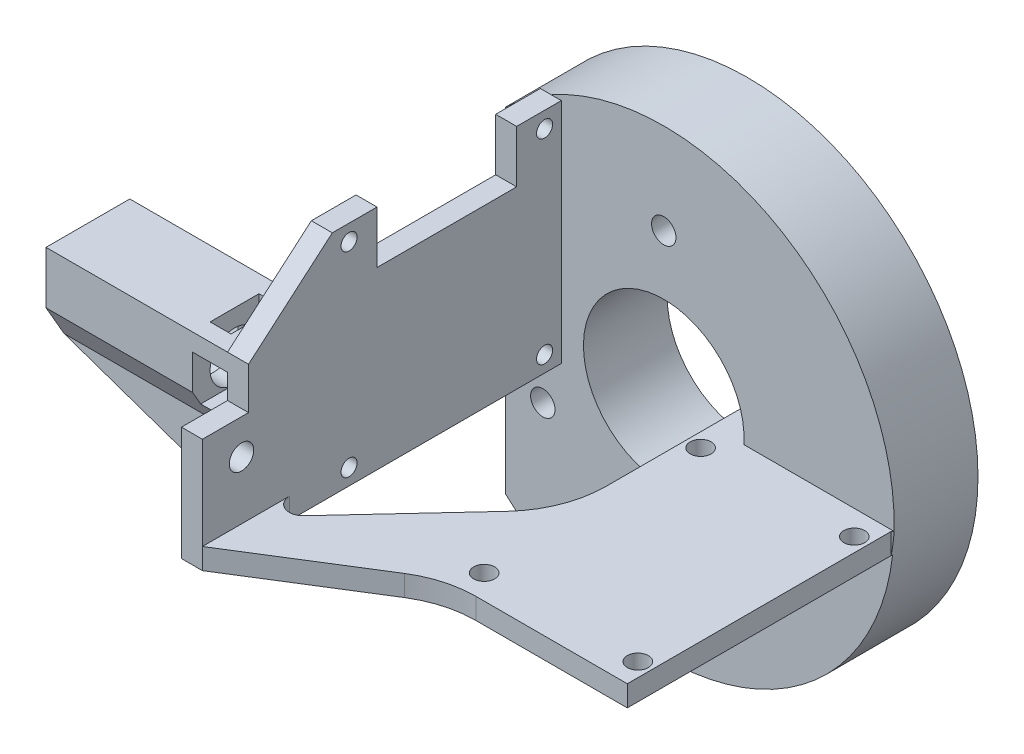
SolidWorks part; units mm, degrees
ref_plane "前视基准面" through (0, 0, 0) normal (0, 0, 1) x (1, 0, 0)
ref_plane "上视基准面" through (0, 0, 0) normal (0, 1, 0) x (1, 0, 0)
ref_plane "右视基准面" through (0, 0, 0) normal (1, 0, 0) x (0, 0, -1)
sketch "草图1" plane through (0, 0, 0) normal (0, 0, 1) x (1, 0, 0)
  circle A0 centre (0, 0) radius 29
  dimension "D1" = 58
extrude "凸台-拉伸1" add sketch "草图1" along normal blind 5
sketch "草图2" plane through (0, 0, 5) normal (0, 0, 1) x (1, 0, 0)
  line L0 (0, 0) -> (0, 20)
  line L1 (0, 0) -> (-17.3205, -10)
  line L2 (0, 0) -> (17.3205, -10)
  circle A0 centre (0, 0) radius 20
  dimension "D1" = 40
  dimension "D2" = 120
  dimension "D3" = 120
sketch "草图3" plane through (0, 0, 5) normal (0, 0, 1) x (1, 0, 0)
  point P0 (0, 20)
  point P3 (-17.3205, -10)
  point P6 (17.3205, -10)
hole_wizard "孔1" positions "草图3" profile "草图4" legacy end condition up to next
sketch "草图4" plane through (0, 20, 5) normal (1, 0, 0) x (0, -1, 0)
  line L0 (0, 0) -> (0, 5)
  line L1 (0, 5) -> (1.75, 5)
  line L2 (1.75, 5) -> (1.75, 0)
  line L3 (1.75, 0) -> (0, 0)
  line L4 (0, 110) -> (0, -10) construction
  dimension "直径" = 3.5
  dimension "深度" = 5
hole_wizard "孔2" positions "草图5" profile "草图6" legacy end condition up to next
sketch "草图5" plane through (0, 0, 5) normal (0, 0, 1) x (1, 0, 0)
  point P0 (0, 0)
sketch "草图6" plane through (0, 0, 5) normal (1, 0, 0) x (0, -1, 0)
  line L0 (0, 0) -> (0, 5)
  line L1 (0, 5) -> (11.5, 5)
  line L2 (11.5, 5) -> (11.5, 0)
  line L3 (11.5, 0) -> (0, 0)
  line L4 (0, 110) -> (0, -10) construction
  dimension "直径" = 23
  dimension "深度" = 5
sketch "草图7" plane through (0, 0, 5) normal (0, 0, 1) x (1, 0, 0)
  line L1 (-28.892, -2.5) -> (28.892, -2.5)
  line L2 (-28.892, -2.5) -> (-28.892, 2.5)
  line L3 (-28.892, 2.5) -> (28.892, 2.5)
  line L4 (28.892, -2.5) -> (28.892, 2.5)
  line L5 (-28.892, -2.5) -> (28.892, 2.5) construction
  line L6 (-28.892, 2.5) -> (28.892, -2.5) construction
  circle A0 centre (0, 0) radius 29 construction
  circle A1 centre (0, 0) radius 11.4884
  circle A2 centre (0, 0) radius 29
  point P0 (0, 0)
  circle M5 centre (0, 0) radius 11.5
  dimension "D2" = 58
  dimension "D1" = 5
extrude "凸台-拉伸3" add sketch "草图7" along normal blind 65 contours L3 L2 L1 M5 | A2
sketch "草图9" plane through (0, 0, 5) normal (0, 0, 1) x (1, 0, 0)
  line L1 (-28.892, 2.5) -> (-29.892, 2.5)
  line L2 (-28.892, 2.5) -> (-28.892, -2.5)
  line L3 (-28.892, -2.5) -> (-29.892, -2.5)
  line L4 (-29.892, 2.5) -> (-29.892, -2.5)
  dimension "D1" = 5
  dimension "D2" = 1
extrude "切除-拉伸1" cut sketch "草图9" against normal blind 10
sketch "草图10" plane through (0, 2.5, 0) normal (0, 1, 0) x (1, 0, 0)
  line L0 (-28.892, -70) -> (-11.225, -70) construction
  line L1 (-28.892, -5) -> (-25.892, -5)
  line L2 (-28.892, -5) -> (-28.892, -70)
  line L3 (-28.892, -70) -> (-25.892, -70)
  line L4 (-25.892, -5) -> (-25.892, -70)
  dimension "D1" = 3
extrude "凸台-拉伸5" add sketch "草图10" along normal blind 10
sketch "草图11" plane through (-28.892, 0, 0) normal (-1, 0, 0) x (0, 0, 1)
  line L0 (10, 7.5) -> (64.4, 7.5) construction
  line L1 (5, 2.5) -> (10, 2.5) construction
  line L2 (5, 2.5) -> (5, 7.5) construction
  line L3 (5, 7.5) -> (10, 7.5) construction
  line L4 (10, 2.5) -> (10, 7.5) construction
  line L5 (57.4, 7.5) -> (57.4, 12.5)
  point P5 (57.4, 7.5)
  dimension "D1" = 5
  dimension "D2" = 5
  dimension "D3" = 54.4
  dimension "D4" = 7
  dimension "D5" = 5
sketch "草图14" plane through (-28.892, 0, 0) normal (-1, 0, 0) x (0, 0, 1)
  point P0 (10, 7.5)
  point P3 (64.4, 7.5)
hole_wizard "孔3" positions "草图14" profile "草图15" legacy end condition up to next
sketch "草图15" plane through (-28.892, 7.5, 10) normal (0, 1, 0) x (0, 0, 1)
  line L0 (0, 0) -> (0, 3)
  line L1 (0, 3) -> (1.75, 3)
  line L2 (1.75, 3) -> (1.75, 0)
  line L3 (1.75, 0) -> (0, 0)
  line L4 (0, 110) -> (0, -10) construction
  dimension "直径" = 3.5
  dimension "深度" = 3
sketch "草图16" plane through (-28.892, 0, 0) normal (-1, 0, 0) x (0, 0, 1)
  line L0 (5, 12.5) -> (70, 12.5) construction
  line L1 (25, 12.5) -> (45, 12.5)
  line L2 (25, 12.5) -> (25, 9.5)
  line L3 (25, 9.5) -> (45, 9.5)
  line L4 (45, 12.5) -> (45, 9.5)
  line L5 (5, -20) -> (5, 20) construction
  dimension "D1" = 20
  dimension "D2" = 20
  dimension "D3" = 3
sketch "草图17" plane through (-28.892, 0, 0) normal (-1, 0, 0) x (0, 0, 1)
  line L0 (5, 0) -> (25, 0) construction
  line L1 (5, 2.5) -> (70, 2.5) construction
  line L2 (5, 2.5) -> (5, -2.5)
  line L3 (5, -2.5) -> (70, -2.5)
  line L4 (70, 2.5) -> (70, -2.5)
  line L5 (25, 0) -> (45, 0) construction
  dimension "D1" = 20
  dimension "D2" = 20
sketch "草图20" plane through (0, 0, 70) normal (0, 0, 1) x (1, 0, 0)
  line L0 (-11.225, 2.5) -> (-11.225, -2.5)
  circle A0 centre (0, 0) radius 11.5
  arc M8 (-11.225, -2.5) -> (-11.225, 2.5) centre (0, 0) cw
extrude "凸台-拉伸6" add sketch "草图20" against normal blind 65 contours L0 M8
sketch "草图21" plane through (-28.892, 0, 0) normal (-1, 0, 0) x (0, 0, 1)
  line L0 (63.4, 11) -> (60.8019, 6.5) construction
  line L1 (51.4, 6.5) -> (63.4, 6.5) construction
  line L2 (51.4, 6.5) -> (51.4, 18.5) construction
  line L3 (51.4, 18.5) -> (63.4, 18.5) construction
  line L4 (63.4, 6.5) -> (63.4, 18.5) construction
  line L5 (51.4, 6.5) -> (63.4, 18.5) construction
  line L6 (51.4, 18.5) -> (63.4, 6.5) construction
  circle A0 centre (57.4, 12.5) radius 5.2 construction
  point P0 (57.4, 12.5)
  dimension "D3" = 10.4
  dimension "D1" = 12
  dimension "D2" = 12
  dimension "D4" = 30
  dimension "D5" = 4.5
sketch "草图22" plane through (-28.892, 0, 0) normal (-1, 0, 0) x (0, 0, 1)
  line L0 (51.4, 6.5) -> (51.4, 18.5) construction
  line L1 (51.4, 12.5) -> (63.4, 12.5)
  line L2 (51.4, 12.5) -> (51.4, 18.5)
  line L3 (51.4, 18.5) -> (63.4, 18.5)
  line L4 (63.4, 12.5) -> (63.4, 18.5)
extrude "凸台-拉伸7" add sketch "草图22" against normal blind 3 contours L2 L1 L4 L3
sketch "草图23" plane through (-28.892, 0, 0) normal (-1, 0, 0) x (0, 0, 1)
  line L0 (60.8019, 6.5) -> (63.4, 11)
  line L1 (51.4, 18.5) -> (63.4, 18.5)
  line L2 (51.4, 18.5) -> (51.4, 6.5)
  line L3 (51.4, 6.5) -> (63.4, 6.5)
  line L4 (63.4, 18.5) -> (63.4, 6.5)
  line M16 (63.4, 12.5) -> (63.4, 18.5)
  line M17 (63.4, 18.5) -> (51.4, 18.5)
  line M18 (51.4, 18.5) -> (51.4, 12.5)
extrude "凸台-拉伸8" add sketch "草图23" along normal blind 8 contours L4 L2 L3 L0 M16 M17 M18
hole_wizard "孔5" positions "草图25" profile "草图26" legacy
sketch "草图25" plane through (-36.892, 0, 0) normal (-1, 0, 0) x (0, 0, 1)
  point P0 (57.4, 12.5)
sketch "草图26" plane through (-36.892, 12.5, 57.4) normal (0, 1, 0) x (0, 0, 1)
  line L0 (0, 0) -> (0, 3)
  line L1 (0, 3) -> (3.5, 3)
  line L2 (3.5, 3) -> (3.5, 0)
  line L3 (3.5, 0) -> (0, 0)
  line L4 (0, 110) -> (0, -10) construction
  dimension "直径" = 7
  dimension "深度" = 3
sketch "草图27" plane through (0, 0, 51.4) normal (0, 0, -1) x (-1, 0, 0)
  line L0 (36.892, 12.5) -> (28.892, 12.5)
  line L1 (36.892, 18.5) -> (36.892, 6.5) construction
  line L3 (28.892, 9) -> (33.892, 9)
  line L4 (28.892, 9) -> (28.892, 16)
  line L5 (28.892, 16) -> (33.892, 16)
  line L6 (33.892, 9) -> (33.892, 16)
  line L7 (28.892, 9) -> (33.892, 16) construction
  line L8 (28.892, 16) -> (33.892, 9) construction
  point P5 (31.392, 12.5)
  line M6 (28.892, 12.5) -> (28.892, 6.5)
  dimension "D1" = 3
  dimension "D2" = 5
  dimension "D3" = 7
extrude "切除-拉伸3" cut sketch "草图27" against normal through all contours L0 L6 L5 L4 | L3 L6 L0 M6
sketch "草图28" plane through (0, 18.5, 0) normal (0, 1, 0) x (1, 0, 0)
  line L0 (-36.892, -57.4) -> (-28.892, -57.4)
  line L1 (-36.892, -63.4) -> (-36.892, -51.4) construction
  line L3 (-33.892, -60.9) -> (-30.892, -60.9)
  line L4 (-33.892, -60.9) -> (-33.892, -53.9)
  line L5 (-33.892, -53.9) -> (-30.892, -53.9)
  line L6 (-30.892, -60.9) -> (-30.892, -53.9)
  line L7 (-33.892, -60.9) -> (-30.892, -53.9) construction
  line L8 (-33.892, -53.9) -> (-30.892, -60.9) construction
  point P5 (-32.392, -57.4)
  dimension "D1" = 3
  dimension "D2" = 3
  dimension "D3" = 7
extrude "切除-拉伸4" cut sketch "草图28" against normal up to next contours L3 L6 L0 L4 | L0 L6 L5 L4
sketch "草图29" plane through (-36.892, 0, 0) normal (-1, 0, 0) x (0, 0, 1)
  line L0 (51.4, 18.5) -> (63.4, 6.5) construction
  line L1 (51.4, 6.5) -> (63.4, 6.5)
  line L2 (51.4, 6.5) -> (51.4, 18.5)
  line L3 (51.4, 18.5) -> (63.4, 18.5)
  line L4 (63.4, 6.5) -> (63.4, 18.5)
  line L5 (51.4, 6.5) -> (63.4, 18.5) construction
  line L6 (51.4, 18.5) -> (63.4, 6.5) construction
  line L7 (60.8019, 6.5) -> (63.4, 11)
  point P0 (57.4, 12.5)
  circle M5 centre (57.4, 12.5) radius 3.5
  line M6 (63.4, 11) -> (63.4, 18.5)
  line M7 (63.4, 18.5) -> (51.4, 18.5)
  line M8 (51.4, 18.5) -> (51.4, 6.5)
  line M9 (51.4, 6.5) -> (60.8019, 6.5)
  line M10 (60.8019, 6.5) -> (63.4, 11)
extrude "凸台-拉伸9" add sketch "草图29" along normal blind 18 contours M10 M6 M7 M8 M9 M5 | M5
sketch "草图30" plane through (-54.892, 0, 0) normal (-1, 0, 0) x (0, 0, 1)
  point P0 (57.4, 12.5)
hole_wizard "孔6" positions "草图30" profile "草图31" legacy
sketch "草图31" plane through (-54.892, 12.5, 57.4) normal (0, 1, 0) x (0, 0, 1)
  line L0 (0, 0) -> (0, 18)
  line L1 (0, 18) -> (5.1, 18)
  line L2 (5.1, 18) -> (5.1, 0)
  line L3 (5.1, 0) -> (0, 0)
  line L4 (0, 110) -> (0, -10) construction
  dimension "直径" = 10.2
  dimension "深度" = 18
sketch "草图32" plane through (0, 6.5, 0) normal (0, -1, 0) x (1, 0, 0)
  line L0 (-28.892, 10) -> (-28.892, 64.4) construction
  line L1 (-54.892, 60.8019) -> (-28.892, 60.8019)
  line L2 (-54.892, 60.8019) -> (-54.892, 55.8019)
  line L3 (-54.892, 55.8019) -> (-28.892, 55.8019)
  line L4 (-28.892, 60.8019) -> (-28.892, 55.8019)
  dimension "D1" = 5
extrude "凸台-拉伸10" add sketch "草图32" along normal blind 9
sketch "草图33" plane through (0, 0, 60.8019) normal (0, 0, 1) x (1, 0, 0)
  line L0 (-54.892, 6.5) -> (-28.892, -2.5)
  line L1 (-28.892, -2.5) -> (-54.892, -2.5)
  line L2 (-54.892, -2.5) -> (-54.892, 6.5)
extrude "切除-拉伸5" cut sketch "草图33" against normal up to next contours L2 L0 L1
sketch "草图36" plane through (-28.892, 0, 0) normal (-1, 0, 0) x (0, 0, 1)
  line L0 (25, 12.5) -> (45, 12.5) construction
  line L1 (18.6, 28.8) -> (51.4, 28.8)
  line L2 (18.6, 28.8) -> (18.6, -3.8)
  line L3 (18.6, -3.8) -> (51.4, -3.8)
  line L4 (51.4, 28.8) -> (51.4, -3.8)
  line L5 (18.6, 28.8) -> (51.4, -3.8) construction
  line L6 (18.6, -3.8) -> (51.4, 28.8) construction
  line L7 (51.4, 6.5) -> (51.4, 18.5) construction
  point P0 (35, 12.5)
  dimension "D2" = 32.6
extrude "凸台-拉伸12" add sketch "草图36" against normal blind 3
sketch "草图38" plane through (0, 0, 0) normal (0, 0, -1) x (-1, 0, 0)
  circle A0 centre (0, 0) radius 29
extrude "切除-拉伸7" cut sketch "草图38" against normal blind 5
sketch "草图39" plane through (0, 0, 5) normal (0, 0, -1) x (-1, 0, 0)
  line L1 (11.225, -2.5) -> (28.892, -2.5)
  line L2 (11.225, -2.5) -> (11.225, 12.5)
  line L3 (11.225, 12.5) -> (28.892, 12.5)
  line L4 (28.892, -2.5) -> (28.892, 12.5)
extrude "切除-拉伸8" cut sketch "草图39" against normal up to surface (13.6 mm away) up to face at (-27.392, 20.65, 18.6)
sketch "草图41" plane through (0, 0, 18.6) normal (0, 0, -1) x (-1, 0, 0)
  line L0 (11.225, -2.5) -> (11.225, 2.5) construction
  circle A0 centre (11.225, 0) radius 33
  dimension "D1" = 66
extrude "凸台-拉伸14" add sketch "草图41" along normal blind 12
sketch "草图42" plane through (0, 0, 6.6) normal (0, 0, -1) x (-1, 0, 0)
  line L0 (11.225, 0) -> (11.225, 20)
  line L1 (11.225, 0) -> (-6.0955, -10)
  line L2 (11.225, 0) -> (28.5455, -10)
  circle A0 centre (11.225, 0) radius 20
  dimension "D1" = 40
  dimension "D2" = 120
  dimension "D3" = 120
sketch "草图45" plane through (0, 0, 6.6) normal (0, 0, -1) x (-1, 0, 0)
  point P0 (11.225, 20)
  point P3 (-6.0955, -10)
  point P6 (28.5455, -10)
hole_wizard "孔8" positions "草图45" profile "草图46" legacy end condition up to next
sketch "草图46" plane through (-11.225, 20, 6.6) normal (1, 0, 0) x (0, 1, 0)
  line L0 (0, 0) -> (0, 12)
  line L1 (0, 12) -> (1.75, 12)
  line L2 (1.75, 12) -> (1.75, 0)
  line L3 (1.75, 0) -> (0, 0)
  line L4 (0, 110) -> (0, -10) construction
  dimension "直径" = 3.5
  dimension "深度" = 12
sketch "草图47" plane through (0, 0, 6.6) normal (0, 0, -1) x (-1, 0, 0)
  point P0 (11.225, 0)
hole_wizard "孔9" positions "草图47" profile "草图48" legacy end condition through all
sketch "草图48" plane through (-11.225, 0, 6.6) normal (1, 0, 0) x (0, 1, 0)
  line L0 (0, 0) -> (0, 63.4)
  line L1 (0, 63.4) -> (11.5, 63.4)
  line L2 (11.5, 63.4) -> (11.5, 0)
  line L3 (11.5, 0) -> (0, 0)
  line L4 (0, 110) -> (0, -10) construction
  dimension "直径" = 23
  dimension "深度" = 63.4
sketch "草图50" plane through (-28.892, 0, 0) normal (-1, 0, 0) x (0, 0, 1)
  line L0 (18.6, 28.8) -> (51.4, -3.8)
  line L2 (21, 26.5) -> (49, 26.5)
  line L3 (21, 26.5) -> (21, -1.5)
  line L4 (21, -1.5) -> (49, -1.5)
  line L5 (49, 26.5) -> (49, -1.5)
  line L6 (21, 26.5) -> (49, -1.5) construction
  line L7 (21, -1.5) -> (49, 26.5) construction
  circle A0 centre (21, 26.5) radius 1.5
  circle A1 centre (49, 26.5) radius 1.5
  circle A2 centre (49, -1.5) radius 1.5
  circle A3 centre (21, -1.5) radius 1.5
  point P4 (35, 12.5)
  dimension "D3" = 3
  dimension "D4" = 3
  dimension "D5" = 3
  dimension "D6" = 3
  dimension "D1" = 28
  dimension "D2" = 28
sketch "草图51" plane through (-28.892, 0, 0) normal (-1, 0, 0) x (0, 0, 1)
  point P0 (21, 26.5)
  point P3 (49, 26.5)
  point P6 (49, -1.5)
  point P9 (21, -1.5)
hole_wizard "孔10" positions "草图51" profile "草图52" legacy end condition through all
sketch "草图52" plane through (-28.892, 26.5, 21) normal (0, 1, 0) x (0, 0, 1)
  line L0 (0, 0) -> (0, 50.6671)
  line L1 (0, 50.6671) -> (1.15, 50.6671)
  line L2 (1.15, 50.6671) -> (1.15, 0)
  line L3 (1.15, 0) -> (0, 0)
  line L4 (0, 110) -> (0, -10) construction
  dimension "直径" = 2.3
  dimension "深度" = 50.6671
sketch "草图53" plane through (-28.892, 0, 0) normal (-1, 0, 0) x (0, 0, 1)
  line L0 (51.4, 28.8) -> (18.6, 28.8) construction
  line L1 (25, 36.3) -> (45, 36.3)
  line L2 (25, 36.3) -> (25, 21.3)
  line L3 (25, 21.3) -> (45, 21.3)
  line L4 (45, 36.3) -> (45, 21.3)
  line L5 (25, 36.3) -> (45, 21.3) construction
  line L6 (25, 21.3) -> (45, 36.3) construction
  point P0 (35, 28.8)
  dimension "D1" = 20
  dimension "D2" = 15
extrude "切除-拉伸9" cut sketch "草图53" against normal blind 3
sketch "草图55" plane through (-25.892, 0, 0) normal (1, 0, 0) x (0, 0, -1)
  line L0 (-51.4, 28.8) -> (-63.4, 18.5)
  line L1 (-63.4, 18.5) -> (-51.4, 18.5)
  line L2 (-51.4, 18.5) -> (-51.4, 28.8)
extrude "凸台-拉伸16" add sketch "草图55" against normal blind 3
sketch "草图56" plane through (0, 2.5, 0) normal (0, 1, 0) x (1, 0, 0)
  line L1 (-25.892, -18.6) -> (-22.4499, -18.6)
  line L2 (-25.892, -18.6) -> (-25.892, -70)
  line L3 (-25.892, -70) -> (-22.4499, -70)
  line L4 (-22.4499, -18.6) -> (-22.4499, -70)
extrude "切除-拉伸10" cut sketch "草图56" against normal through all
sketch "草图57" plane through (0, 0, 51.4) normal (0, 0, 1) x (1, 0, 0)
  line L0 (-28.892, -2.5) -> (-25.892, -2.5) construction
  line L1 (-28.892, -3.8) -> (-25.892, -3.8)
  line L2 (-28.892, -3.8) -> (-28.892, -2.5)
  line L3 (-28.892, -2.5) -> (-25.892, -2.5)
  line L4 (-25.892, -3.8) -> (-25.892, -2.5)
  line L5 (-25.892, 28.8) -> (-25.892, -3.8) construction
extrude "凸台-拉伸17" add sketch "草图57" along normal up to surface (18.6 mm away) up to face at (-27.392, 5, 70)
sketch "草图58" plane through (0, -3.8, 0) normal (0, -1, 0) x (1, 0, 0)
  line L0 (-25.892, 70) -> (21.775, 18.6)
  line L1 (-25.892, 62.6468) -> (14.9559, 18.6)
  line L2 (-25.892, 18.6) -> (-25.892, 70) construction
  line L3 (21.775, 18.6) -> (-44.225, 18.6) construction
  line L4 (-25.892, 70) -> (-25.892, 62.6468)
  line L5 (14.9559, 18.6) -> (21.775, 18.6)
  dimension "D1" = 5
extrude "凸台-拉伸18" add sketch "草图58" against normal blind 3
ref_plane "基准面1" through (-13.892, 0, 0) normal (1, 0, 0) x (0, 0, -1)
sketch "草图62" plane through (0, 0, 6.6) normal (0, 0, -1) x (-1, 0, 0)
  line L0 (33.892, 23.9834) -> (33.892, -23.9834)
  line L1 (11.225, 0) -> (11.225, 20) construction
  line L2 (13.892, 17.93) -> (13.892, -17.93) construction
  circle A0 centre (11.225, 0) radius 33 construction
  circle A1 centre (11.225, 0) radius 33
  dimension "D2" = 66
  dimension "D1" = 20
extrude "切除-拉伸11" cut sketch "草图62" against normal up to next contours L0 A1
sketch "草图63" plane through (0, 0, 18.6) normal (0, 0, 1) x (1, 0, 0)
  line L0 (21.775, -2.3) -> (0.0427, -2.3)
  line L1 (21.775, -0.8) -> (21.775, -3.8) construction
  line L2 (21.775, -0.8) -> (-25.892, -0.8) construction
  line L4 (21.5555, -3.8) -> (-4.4445, -3.8)
  line L9 (21.5555, -3.8) -> (21.5555, -0.8)
  line L10 (21.5555, -0.8) -> (-4.4445, -0.8)
  line L11 (-4.4445, -3.8) -> (-4.4445, -0.8)
  circle A0 centre (-11.225, 0) radius 11.5 construction
  point P13 (21.5555, -3.8)
  dimension "D1" = 26
extrude "凸台-拉伸21" add sketch "草图63" along normal blind 38 contours L4 L11 L10 L9
sketch "草图64" plane through (0, -0.8, 0) normal (0, 1, 0) x (1, 0, 0)
  line L0 (-4.4445, -18.6) -> (21.5555, -56.6)
  line L2 (-2.4445, -53.1) -> (19.5555, -53.1)
  line L3 (-2.4445, -53.1) -> (-2.4445, -22.1)
  line L4 (-2.4445, -22.1) -> (19.5555, -22.1)
  line L5 (19.5555, -53.1) -> (19.5555, -22.1)
  line L6 (-2.4445, -53.1) -> (19.5555, -22.1) construction
  line L7 (-2.4445, -22.1) -> (19.5555, -53.1) construction
  point P4 (8.5555, -37.6)
  dimension "D1" = 22
  dimension "D2" = 31
sketch "草图65" plane through (0, -0.8, 0) normal (0, 1, 0) x (1, 0, 0)
  point P0 (-2.4445, -22.1)
  point P3 (19.5555, -22.1)
  point P6 (-2.4445, -53.1)
  point P9 (19.5555, -53.1)
hole_wizard "孔11" positions "草图65" profile "草图66" legacy end condition up to next
sketch "草图66" plane through (-2.4445, -0.8, 22.1) normal (1, 0, 0) x (0, 0, 1)
  line L0 (0, 0) -> (0, 3)
  line L1 (0, 3) -> (1.5, 3)
  line L2 (1.5, 3) -> (1.5, 0)
  line L3 (1.5, 0) -> (0, 0)
  line L4 (0, 110) -> (0, -10) construction
  dimension "直径" = 3
  dimension "深度" = 3
sketch "草图67" plane through (0, -0.8, 0) normal (0, 1, 0) x (1, 0, 0)
  line L0 (-25.892, -70) -> (-4.4445, -56.6)
  line L1 (-4.4445, -56.6) -> (-4.4445, -46.8728)
  line L2 (-4.4445, -46.8728) -> (-25.892, -70)
extrude "凸台-拉伸22" add sketch "草图67" against normal blind 3
sketch "草图68" plane through (0, 0, 18.6) normal (0, 0, 1) x (1, 0, 0)
  line L0 (21.4349, -4.7257) -> (29.5362, -6.7818)
  line L1 (21.716, 1.9729) -> (30.0494, 1.9729)
  circle A0 centre (-11.225, 0) radius 33
  circle A1 centre (-11.225, 0) radius 41.3215
  arc M7 (21.7653, -0.8) -> (-27.3358, 28.8) centre (-11.225, 0) ccw
  arc M14 (-33.892, -23.9834) -> (21.5555, -3.8) centre (-11.225, 0) ccw
  dimension "D1" = 66
  dimension "D2" = 82.6431
extrude "切除-拉伸13" cut sketch "草图68" along normal blind 4 contours L0 A1 L1 A0 M7 M14
fillet "圆角1" radius 15 2 edges at (-4.4445, -2.3, 39.5197) (-4.4445, -2.3, 56.6)
fillet "圆角2" radius 2 1 edges at (-25.892, -2.3, 62.6468)
sketch "草图69" plane through (0, 0, 18.6) normal (0, 0, -1) x (-1, 0, 0)
  line L0 (0.3709, -3.8) -> (4.4445, -3.8)
  line L1 (4.4445, -3.8) -> (4.4445, -0.8)
  line L2 (4.4445, -0.8) -> (-0.2472, -0.8)
  circle A0 centre (11.225, 0) radius 11.5
  line M1 (4.4445, -0.8) -> (-0.2472, -0.8)
  arc M2 (-0.2472, -0.8) -> (0.3709, -3.8) centre (11.225, 0) ccw
  line M3 (0.3709, -3.8) -> (4.4445, -3.8)
  line M4 (4.4445, -3.8) -> (4.4445, -0.8)
extrude "凸台-拉伸23" add sketch "草图69" along normal blind 12 contours M4 M1 M2 M3
